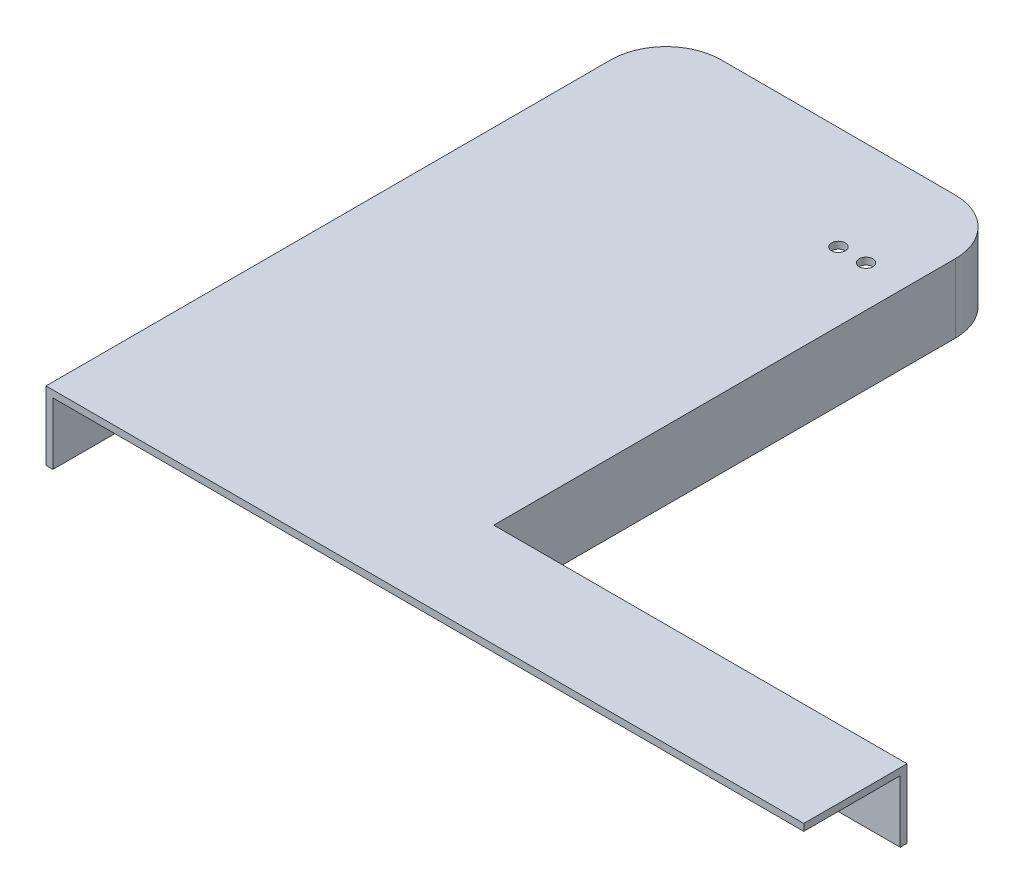
SolidWorks part; units mm, degrees
material "ABS"
ref_plane "Front Plane" through (0, 0, 0) normal (0, 0, 1) x (1, 0, 0)
ref_plane "Top Plane" through (0, 0, 0) normal (0, 1, 0) x (1, 0, 0)
ref_plane "Right Plane" through (0, 0, 0) normal (1, 0, 0) x (0, 0, -1)
sketch "Sketch1" plane through (0, 0, 0) normal (0, 1, 0) x (1, 0, 0)
  line L1 (-279.4, -203.2) -> (279.4, -203.2)
  line L2 (-279.4, -203.2) -> (-279.4, 203.2)
  line L3 (-279.4, 203.2) -> (279.4, 203.2)
  line L4 (279.4, -203.2) -> (279.4, 203.2)
  line L5 (-279.4, -203.2) -> (279.4, 203.2) construction
  line L6 (-279.4, 203.2) -> (279.4, -203.2) construction
  line L7 (-152.4, 203.2) -> (152.4, 203.2)
  line L8 (-152.4, 203.2) -> (-152.4, 12.7)
  line L9 (-152.4, 12.7) -> (152.4, 12.7)
  line L10 (152.4, 203.2) -> (152.4, 12.7)
  point P0 (0, 0)
  dimension "D1" = 558.8
  dimension "D2" = 406.4
  dimension "D3" = 127
  dimension "D4" = 127
  dimension "D5" = 190.5
extrude "Boss-Extrude1" add sketch "Sketch1" along normal blind 25.4 contours L3 L10 L9 L8 L2 L1 L4
fillet "Fillet1" radius 20.32 4 edges at (279.4, 12.7, -203.2) (152.4, 12.7, -203.2) (-279.4, 12.7, -203.2) (-152.4, 12.7, -203.2)
shell "Shell1" thickness 2.54
sketch "Sketch2" plane through (0, 25.4, 0) normal (0, 1, 0) x (1, 0, 0)
  line L0 (-317.2722, 165.1) -> (360.7838, 165.1) construction
  line L1 (-279.4, -203.2) -> (279.4, -203.2) construction
  line L2 (152.4, 182.88) -> (152.4, 12.7) construction
  line L3 (-152.4, 182.88) -> (-152.4, 12.7) construction
  circle A0 centre (-177.72, 165.1) radius 2.54
  circle A1 centre (-167.56, 165.1) radius 2.54
  circle A2 centre (167.56, 165.1) radius 2.54
  circle A3 centre (177.72, 165.1) radius 2.54
  point P12 (157.4, 165.1)
  point P13 (-157.4, 165.1)
  dimension "D2" = 10.16
  dimension "D8" = 5.08
  dimension "D1" = 368.3
  dimension "D3" = 10.16
  dimension "D4" = 10.16
  dimension "D5" = 10.16
  dimension "D6" = 5
  dimension "D7" = 5
extrude "Cut-Extrude1" cut sketch "Sketch2" against normal through all
sketch "Sketch3" plane through (279.4, 0, 0) normal (1, 0, 0) x (0, 0, -1)
  line L1 (-203.2, 25.4) -> (229.0636, 25.4)
  line L2 (-203.2, 25.4) -> (-203.2, -7.7359)
  line L3 (-203.2, -7.7359) -> (229.0636, -7.7359)
  line L4 (229.0636, 25.4) -> (229.0636, -7.7359)
extrude "Cut-Extrude2" cut sketch "Sketch3" against normal blind 279.4
sketch "Sketch4" plane through (0, 0, 203.2) normal (0, 0, 1) x (1, 0, 0)
  line L1 (-279.4, 0) -> (93.1618, 0)
  line L2 (-279.4, 0) -> (-279.4, 70.3317)
  line L3 (-279.4, 70.3317) -> (93.1618, 70.3317)
  line L4 (93.1618, 0) -> (93.1618, 70.3317)
extrude "Cut-Extrude3" cut sketch "Sketch4" against normal blind 177.8
